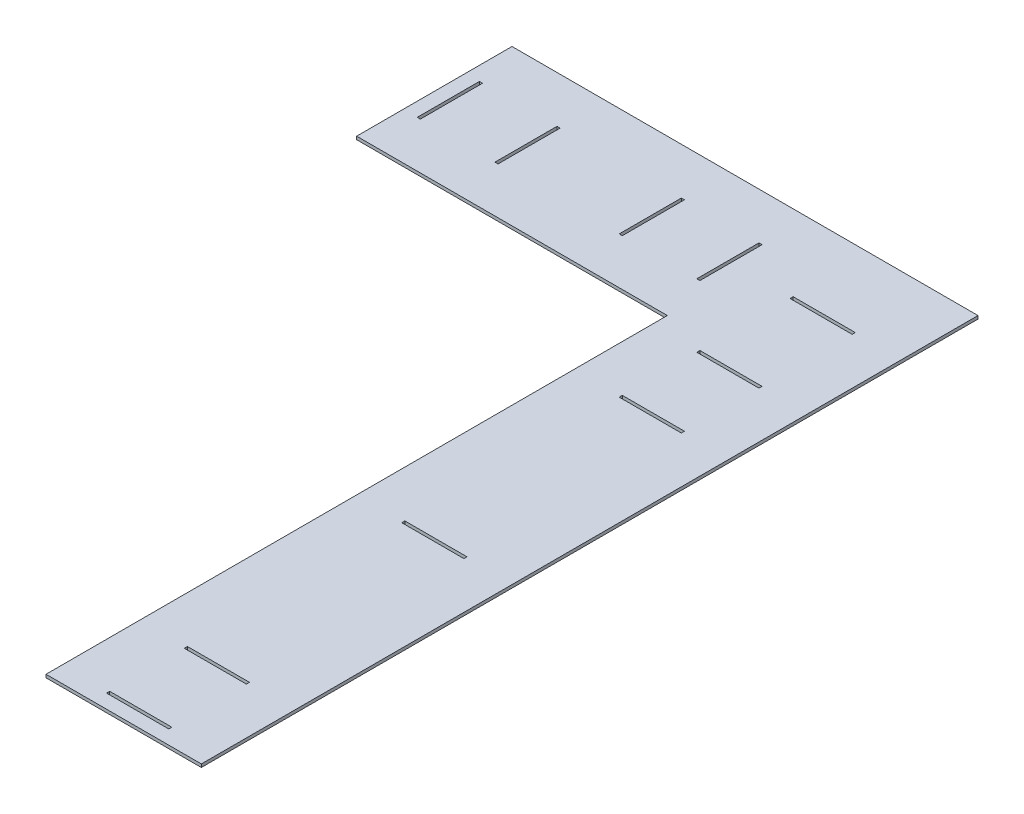
SolidWorks part; units mm, degrees
ref_plane "Front Plane" through (0, 0, 0) normal (0, 0, 1) x (1, 0, 0)
ref_plane "Top Plane" through (0, 0, 0) normal (0, 1, 0) x (1, 0, 0)
ref_plane "Right Plane" through (0, 0, 0) normal (1, 0, 0) x (0, 0, -1)
sketch "Sketch1" plane through (0, 0, 0) normal (0, 1, 0) x (1, 0, 0)
  line L6 (0, 0) -> (100, 0)
  line L7 (100, 0) -> (100, -200)
  line L8 (100, -200) -> (150, -200)
  line L9 (150, -200) -> (150, 50)
  line L14 (150, 50) -> (0, 50)
  line L15 (0, 50) -> (0, 0)
  line L16 (125, -200) -> (125, 50) construction
  line L18 (0, 25) -> (150, 25) construction
  line L19 (4.5, 15) -> (5.5, 15)
  line L20 (4.5, 15) -> (4.5, 35)
  line L21 (4.5, 35) -> (5.5, 35)
  line L22 (5.5, 15) -> (5.5, 35)
  line L23 (4.5, 15) -> (5.5, 35) construction
  line L24 (4.5, 35) -> (5.5, 15) construction
  line L25 (29.5, 15) -> (30.5, 15)
  line L26 (29.5, 15) -> (29.5, 35)
  line L27 (29.5, 35) -> (30.5, 35)
  line L28 (30.5, 15) -> (30.5, 35)
  line L29 (29.5, 15) -> (30.5, 35) construction
  line L30 (29.5, 35) -> (30.5, 15) construction
  line L31 (94.5, 35) -> (95.5, 35)
  line L32 (94.5, 35) -> (94.5, 15)
  line L33 (94.5, 15) -> (95.5, 15)
  line L34 (95.5, 35) -> (95.5, 15)
  line L35 (94.5, 35) -> (95.5, 15) construction
  line L36 (94.5, 15) -> (95.5, 35) construction
  line L37 (115, -4.5) -> (135, -4.5)
  line L38 (115, -4.5) -> (115, -5.5)
  line L39 (115, -5.5) -> (135, -5.5)
  line L40 (135, -4.5) -> (135, -5.5)
  line L41 (115, -4.5) -> (135, -5.5) construction
  line L42 (115, -5.5) -> (135, -4.5) construction
  line L43 (115, -29.5) -> (135, -29.5)
  line L44 (115, -29.5) -> (115, -30.5)
  line L45 (115, -30.5) -> (135, -30.5)
  line L46 (135, -29.5) -> (135, -30.5)
  line L47 (115, -29.5) -> (135, -30.5) construction
  line L48 (115, -30.5) -> (135, -29.5) construction
  line L49 (115, -99.5) -> (135, -99.5)
  line L50 (115, -99.5) -> (115, -100.5)
  line L51 (115, -100.5) -> (135, -100.5)
  line L52 (135, -99.5) -> (135, -100.5)
  line L53 (115, -99.5) -> (135, -100.5) construction
  line L54 (115, -100.5) -> (135, -99.5) construction
  line L55 (115, -195.5) -> (135, -195.5)
  line L56 (115, -195.5) -> (115, -194.5)
  line L57 (115, -194.5) -> (135, -194.5)
  line L58 (135, -195.5) -> (135, -194.5)
  line L59 (115, -195.5) -> (135, -194.5) construction
  line L60 (115, -194.5) -> (135, -195.5) construction
  line L61 (115, -169.5) -> (135, -169.5)
  line L62 (115, -169.5) -> (115, -170.5)
  line L63 (115, -170.5) -> (135, -170.5)
  line L64 (135, -169.5) -> (135, -170.5)
  line L65 (115, -169.5) -> (135, -170.5) construction
  line L66 (115, -170.5) -> (135, -169.5) construction
  line L67 (115, 24.5) -> (135, 24.5)
  line L68 (115, 24.5) -> (115, 25.5)
  line L69 (115, 25.5) -> (135, 25.5)
  line L70 (135, 24.5) -> (135, 25.5)
  line L71 (115, 24.5) -> (135, 25.5) construction
  line L72 (115, 25.5) -> (135, 24.5) construction
  line L73 (70.5, 15) -> (69.5, 15)
  line L74 (70.5, 15) -> (70.5, 35)
  line L75 (70.5, 35) -> (69.5, 35)
  line L76 (69.5, 15) -> (69.5, 35)
  line L77 (70.5, 15) -> (69.5, 35) construction
  line L78 (70.5, 35) -> (69.5, 15) construction
  point P9 (5, 25)
  point P16 (30, 25)
  point P22 (95, 25)
  point P27 (125, -5)
  point P32 (125, -30)
  point P37 (125, -100)
  point P42 (125, -195)
  point P47 (125, -170)
  point P52 (125, 25)
  point P58 (70, 25)
  dimension "D1" = 50
  dimension "D2" = 50
  dimension "D3" = 100
  dimension "D4" = 200
  dimension "D5" = 5
  dimension "D6" = 25
  dimension "D7" = 5
  dimension "D8" = 25
  dimension "D9" = 5
  dimension "D10" = 25
  dimension "D11" = 5
  dimension "D12" = 25
  dimension "D13" = 70
  dimension "D14" = 70
  dimension "D15" = 1
  dimension "D16" = 20
  dimension "D17" = 20
extrude "Boss-Extrude1" add sketch "Sketch1" along normal blind 1
